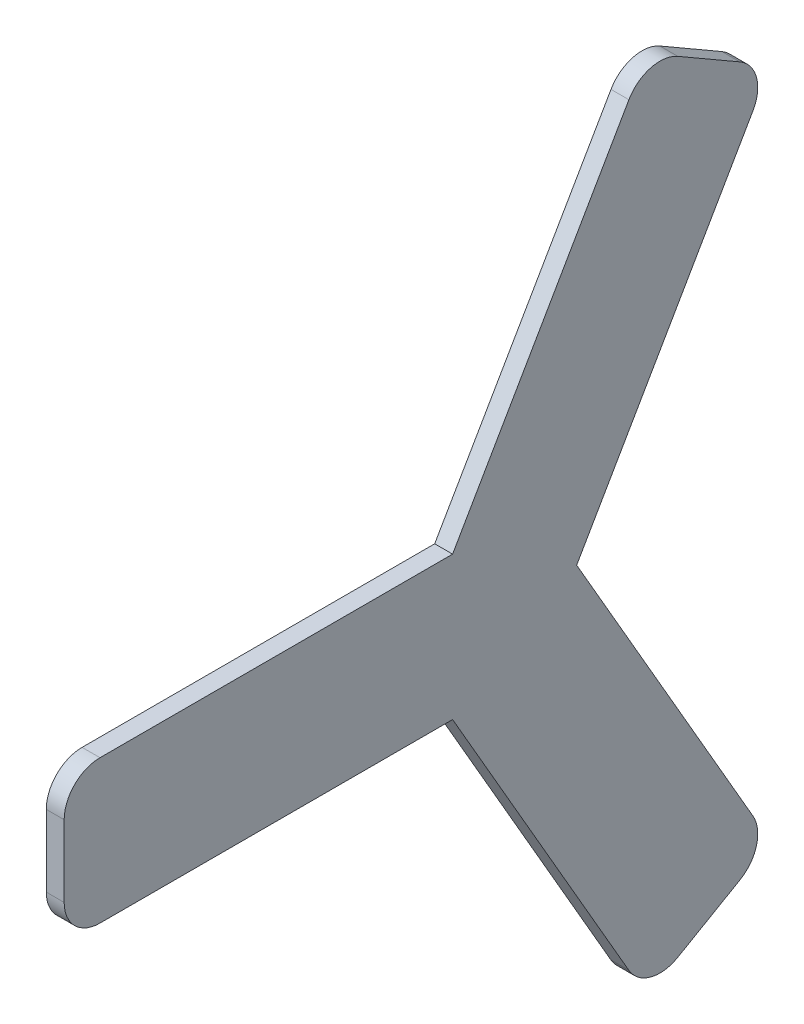
SolidWorks part; units mm, degrees
ref_plane "Front Plane" through (0, 0, 0) normal (1, 0, 0) x (0, 1, 0)
ref_plane "Top Plane" through (0, 0, 0) normal (0, 0, 1) x (0, 1, 0)
ref_plane "Right Plane" through (0, 0, 0) normal (0, 1, 0) x (-1, 0, 0)
sketch "Sketch1" plane through (0, 0, 0) normal (1, 0, 0) x (0, 1, 0)
  line L2 (0, 0) -> (0, 12)
  point P0 (1.3729, 10.3012)
  dimension "D1" = 12
extrude "Extrude-Thin2" add sketch "Sketch1" along normal blind 0.5 thin thin type mid plane wall 4
fillet "Fillet2" radius 1 2 edges at (0.25, -2, 12) (0.25, 2, 12)
sketch "Sketch2" plane through (0, 0, 0) normal (0, 0, 1) x (0, 1, 0)
  line L0 (0, 0) -> (0, -0.5) construction
  line L1 (-1, -0.5) -> (1, -0.5) construction
pattern_circular "CirPattern1" count 3 over 360 about axis through (0, 0, 0) along (1, 0, 0) of "Extrude-Thin2", "Fillet2"
